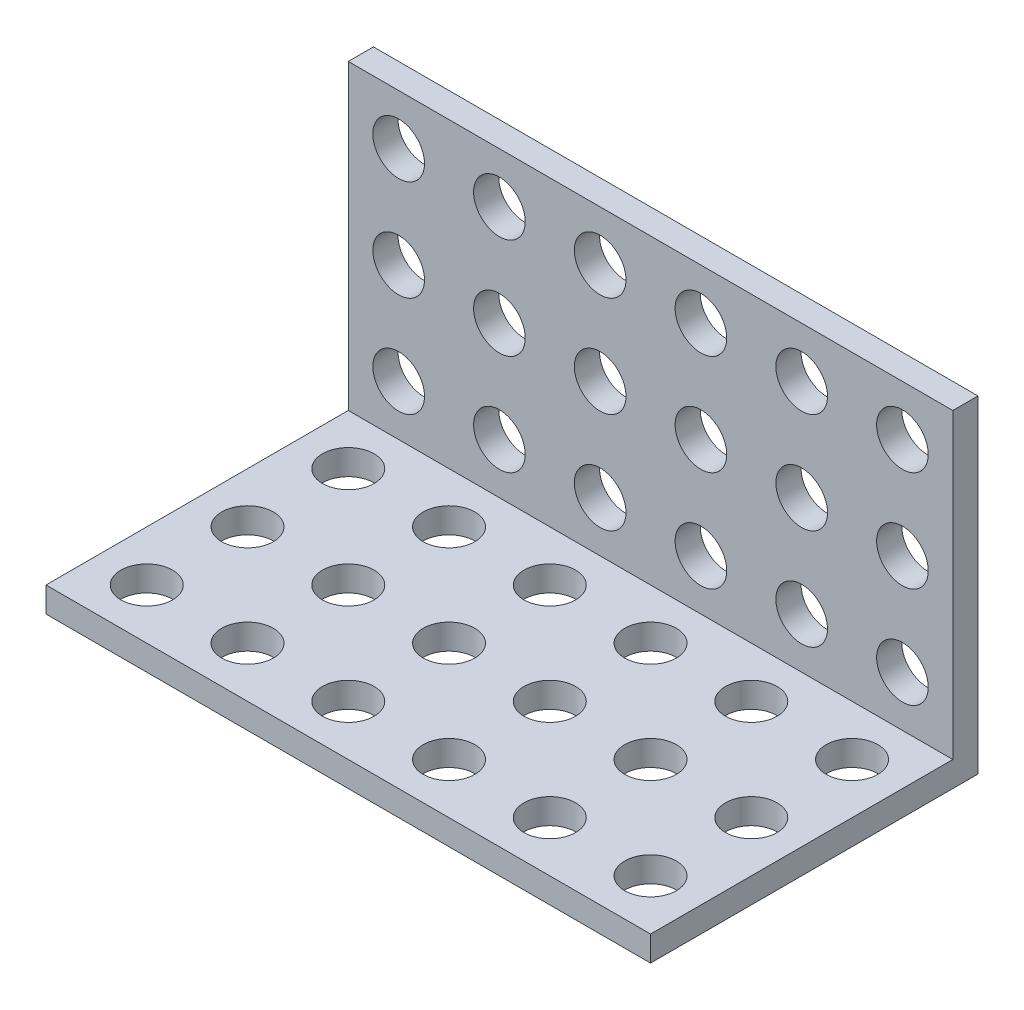
SolidWorks part; units mm, degrees
ref_plane "Front Plane" through (0, 0, 0) normal (0, 0, 1) x (1, 0, 0)
ref_plane "Top Plane" through (0, 0, 0) normal (0, 1, 0) x (1, 0, 0)
ref_plane "Right Plane" through (0, 0, 0) normal (1, 0, 0) x (0, 0, -1)
sketch "Sketch3" plane through (0, 0, 0) normal (1, 0, 0) x (0, 0, -1)
  line L0 (0, 0) -> (0, 26)
  line L1 (0, 0) -> (-26, 0)
  line L2 (-26, 0) -> (-26, 2)
  line L3 (0, 26) -> (-2, 26)
  line L4 (-26, 2) -> (-2, 2)
  line L5 (-2, 2) -> (-2, 26)
extrude "Boss-Extrude1" add sketch "Sketch3" along normal blind 48
hole_wizard "Ø4.1 (4.1) Diameter Hole1" positions "Sketch5" profile "Sketch4" hole size "Ø4.1" standard "ANSI Metric" end condition through all
sketch "Sketch5" plane through (0, 0, 2) normal (0, 0, 1) x (1, 0, 0)
  point P0 (4, 22)
sketch "Sketch4" plane through (4, 22, 2) normal (1, 0, 0) x (0, -1, 0)
  line L0 (0, 0) -> (0, 2)
  line L1 (0, 2) -> (2.05, 2)
  line L2 (2.05, 2) -> (2.05, 0)
  line L5 (2.05, 0) -> (0, 0)
  line L11 (0, -6.35) -> (0, 107.95) construction
  dimension "Thru Hole Dia." = 4.1
  dimension "Thru Hole Depth" = 2
pattern_linear "LPattern1" count 6 spacing 8 along (1, 0, 0) count 3 spacing 8 along (0, -1, 0) of "Ø4.1 (4.1) Diameter Hole1"
ref_plane "Mirroring Plane" through (0, 0, 0) normal (0, -0.7071, 0.7071) x (-1, 0, 0)
mirror "Mirror1" about plane through (0, 0, 0) normal (0, -0.7071, 0.7071) of "LPattern1", "Ø4.1 (4.1) Diameter Hole1"
